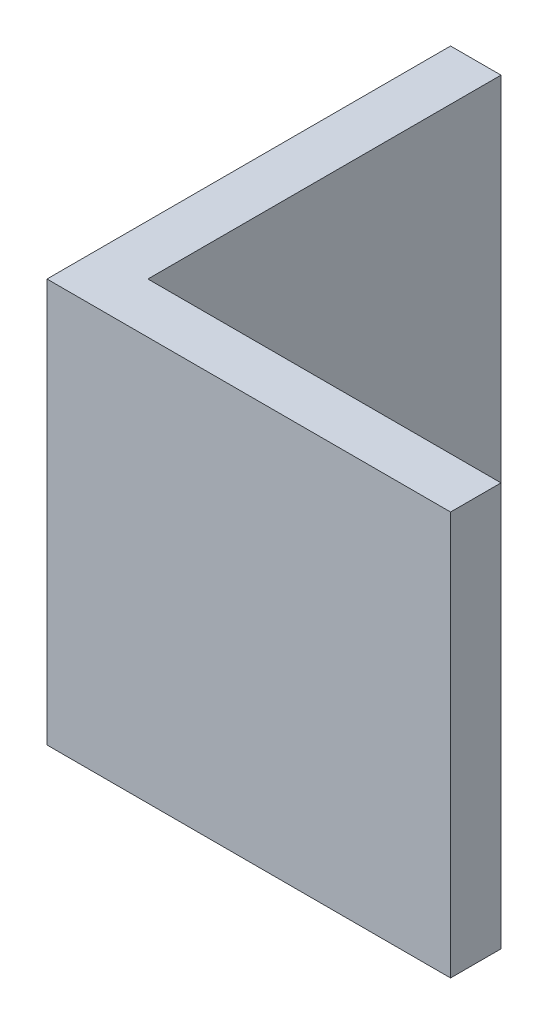
SolidWorks part; units mm, degrees
ref_plane "Front Plane" through (0, 0, 0) normal (0, 0, 1) x (1, 0, 0)
ref_plane "Top Plane" through (0, 0, 0) normal (0, 1, 0) x (1, 0, 0)
ref_plane "Right Plane" through (0, 0, 0) normal (1, 0, 0) x (0, 0, -1)
sketch "Sketch1" plane through (0, 0, 0) normal (0, 1, 0) x (1, 0, 0)
  line L0 (0, 0) -> (0, 25.4)
  line L1 (0, 0) -> (25.4, 0)
  line L2 (3.175, 3.175) -> (25.4, 3.175)
  line L3 (3.175, 3.175) -> (3.175, 25.4)
  line L4 (0, 25.4) -> (3.175, 25.4)
  line L5 (25.4, 3.175) -> (25.4, 0)
  dimension "D1" = 25.4
  dimension "D2" = 25.4
  dimension "D3" = 3.175
extrude "Boss-Extrude1" add sketch "Sketch1" along normal blind 25.4
